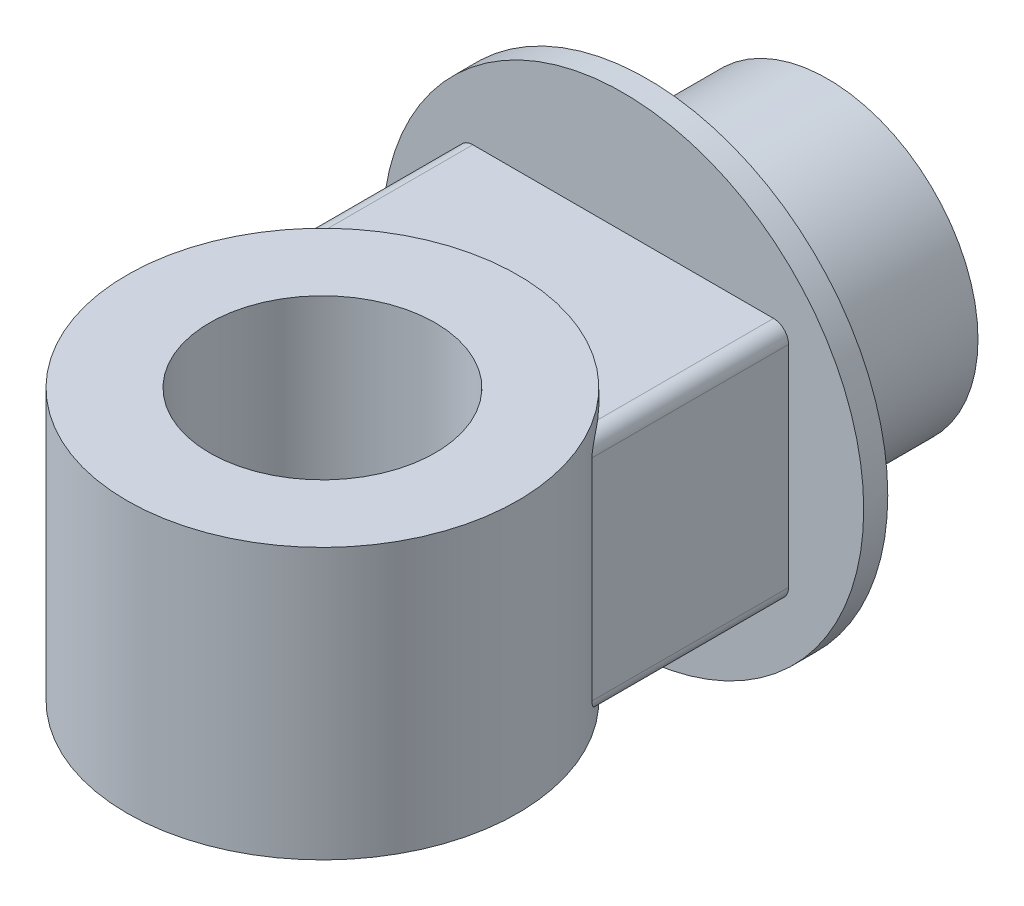
SolidWorks part; units mm, degrees
ref_plane "Front Plane" through (0, 0, 0) normal (0, 0, 1) x (1, 0, 0)
ref_plane "Top Plane" through (0, 0, 0) normal (0, 1, 0) x (1, 0, 0)
ref_plane "Right Plane" through (0, 0, 0) normal (1, 0, 0) x (0, 0, -1)
sketch "Sketch1" plane through (0, 0, 0) normal (0, 0, 1) x (1, 0, 0)
  circle A0 centre (0, 0) radius 100
  dimension "D1" = 200
extrude "Boss-Extrude1" add sketch "Sketch1" along normal blind 120
sketch "Sketch2" plane through (0, 0, 120) normal (0, 0, 1) x (1, 0, 0)
  circle A0 centre (0, 0) radius 160
  dimension "D1" = 320
extrude "Boss-Extrude2" add sketch "Sketch2" along normal blind 16
sketch "Sketch4" plane through (0, 0, 0) normal (0, 1, 0) x (1, 0, 0)
  line L0 (-160, -136) -> (160, -136) construction
  circle A0 centre (0, -336) radius 75
  circle A1 centre (0, -336) radius 130
  dimension "D1" = 150
  dimension "D2" = 260
  dimension "D3" = 200
extrude "Boss-Extrude3" add sketch "Sketch4" along normal mid plane 180 separate body
sketch "Sketch5" plane through (0, 0, 136) normal (0, 0, 1) x (1, 0, 0)
  line L1 (-110, 80) -> (110, 80)
  line L2 (-110, 80) -> (-110, -80)
  line L3 (-110, -80) -> (110, -80)
  line L4 (110, 80) -> (110, -80)
  line L5 (-110, 80) -> (110, -80) construction
  line L6 (-110, -80) -> (110, 80) construction
  point P0 (0, 0)
  dimension "D1" = 220
  dimension "D2" = 160
extrude "Boss-Extrude4" add sketch "Sketch5" along normal up to next
fillet "Fillet1" radius 10 4 edges at (-110, -80, 201.359) (110, -80, 201.359) (-110, 80, 201.359) (110, 80, 201.359)
